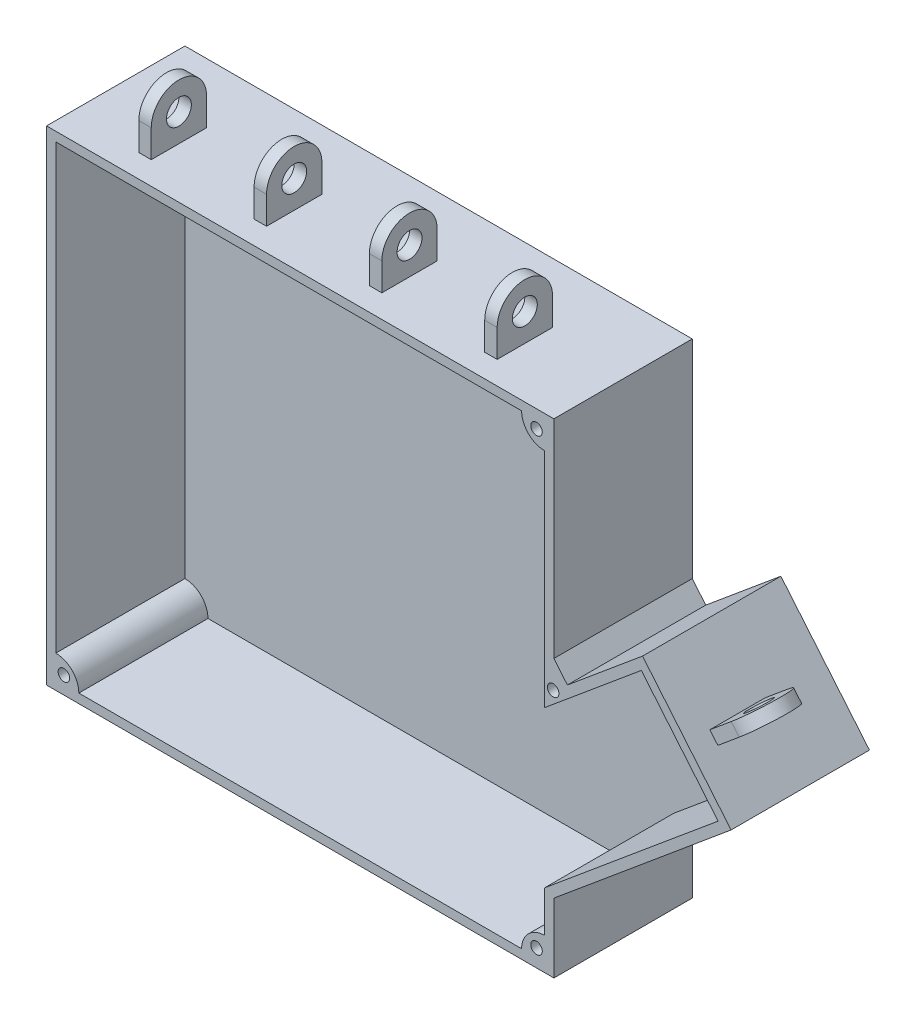
SolidWorks part; units mm, degrees
ref_plane "Front Plane" through (0, 0, 0) normal (0, 0, 1) x (1, 0, 0)
ref_plane "Top Plane" through (0, 0, 0) normal (0, 1, 0) x (1, 0, 0)
ref_plane "Right Plane" through (0, 0, 0) normal (1, 0, 0) x (0, 0, -1)
sketch "Sketch2" plane through (0, 0, 0) normal (0, 0, 1) x (1, 0, 0)
  line L0 (25, 95) -> (45, 95) construction
  line L1 (0, 0) -> (85, 0) construction
  line L2 (0, 0) -> (0, 50) construction
  line L3 (0, 50) -> (85, 50) construction
  line L4 (85, 0) -> (85, 50) construction
  line L5 (0, 95) -> (20, 95) construction
  line L6 (0, 95) -> (0, 55) construction
  line L7 (0, 55) -> (20, 55) construction
  line L8 (20, 95) -> (20, 55) construction
  line L9 (25, 95) -> (25, 55) construction
  line L10 (25, 55) -> (45, 55) construction
  line L11 (45, 95) -> (45, 55) construction
  line L12 (50, 95) -> (70, 95) construction
  line L13 (50, 95) -> (50, 55) construction
  line L14 (50, 55) -> (70, 55) construction
  line L15 (70, 95) -> (70, 55) construction
  line L16 (75, 95) -> (95, 95) construction
  line L17 (75, 95) -> (75, 55) construction
  line L18 (75, 55) -> (95, 55) construction
  line L19 (95, 95) -> (95, 55) construction
  line L24 (10, 95) -> (10, 55) construction
  line L26 (35, 95) -> (35, 55) construction
  line L28 (60, 95) -> (60, 55) construction
  line L29 (85, 95) -> (85, 55) construction
  dimension "D1" = 50
  dimension "D2" = 85
  dimension "D3" = 40
  dimension "D4" = 20
  dimension "D5" = 40
  dimension "D6" = 20
  dimension "D7" = 40
  dimension "D8" = 20
  dimension "D9" = 40
  dimension "D10" = 20
  dimension "D13" = 5
  dimension "D14" = 5
  dimension "D15" = 5
  dimension "D16" = 5
  dimension "D17" = 5
  dimension "D18" = 5
  dimension "D19" = 5
sketch "Sketch3" plane through (0, 0, 0) normal (0, 0, 1) x (1, 0, 0)
  line L0 (0, 0) -> (0, 50) construction
  line L9 (-5, -5) -> (105, -5)
  line L10 (-5, -5) -> (-5, 100)
  line L11 (-5, 100) -> (105, 100)
  line L12 (105, -5) -> (105, 10)
  line L13 (0, 0) -> (85, 0) construction
  line L14 (105, 10) -> (143.4182, 42.0006)
  line L15 (143.4182, 42.0006) -> (124.2179, 65.0515)
  line L16 (124.2179, 65.0515) -> (107.929, 51.4836)
  line L17 (107.929, 51.4836) -> (105, 55)
  line L18 (105, 55) -> (105, 100)
  dimension "D1" = 110
  dimension "D2" = 105
  dimension "D3" = 5
  dimension "D4" = 5
  dimension "D5" = 50
  dimension "D6" = 15
  dimension "D7" = 45
  dimension "D8" = 30
extrude "Boss-Extrude1" add sketch "Sketch3" along normal blind 30
sketch "Sketch4" plane through (0, 0, 0) normal (1, 0, 0) x (0, 0, -1)
  line L0 (-30, 100) -> (0, 100) construction
  line L1 (-25, 100) -> (-13, 100)
  line L2 (-25, 100) -> (-25, 106)
  line L4 (-13, 100) -> (-13, 106)
  line L5 (-30, 55) -> (-30, 100) construction
  arc A2 (-13, 106) -> (-25, 106) centre (-19, 106) ccw
  circle A3 centre (-19, 106) radius 2.7
  dimension "D4" = 5.4
  dimension "D1" = 5
  dimension "D2" = 6
  dimension "D3" = 12
shell "Shell1" thickness 2
sketch "Sketch9" plane through (0, 0, 2) normal (0, 0, 1) x (1, 0, 0)
  line L4 (92.8415, 32.4092) -> (123.5761, 58.0097) construction
  line L5 (123.5761, 58.0097) -> (136.3764, 42.6424) construction
  line L6 (136.3764, 42.6424) -> (105.6418, 17.0419) construction
  line L7 (105.6418, 17.0419) -> (92.8415, 32.4092) construction
  line L11 (140.6015, 42.2573) -> (123.9612, 62.2348) construction
  line L12 (123.9612, 62.2348) -> (107.6723, 48.6669) construction
  line L13 (129.9762, 50.326) -> (99.2416, 24.7255) construction
  dimension "D1" = 20
  dimension "D2" = 3
  dimension "D3" = 3
  dimension "D4" = 40
ref_plane "Plane6" through (0, 0, 30) normal (0, 0, 1) x (1, 0, 0)
sketch "Sketch10" plane through (0, 0, 30) normal (0, 0, 1) x (1, 0, 0)
  line L0 (103, 98) -> (-3, 98) construction
  line L1 (-3, 98) -> (-3, -3) construction
  line L2 (103, 54.2762) -> (103, 98) construction
  line L3 (103, -3) -> (103, 10.937) construction
  line L4 (-3, -3) -> (103, -3) construction
  line L5 (-3, -3) -> (103, -3) construction
  line L6 (98, 98) -> (103, 98)
  line L7 (103, 98) -> (103, 93)
  line L8 (103, 2) -> (103, -3)
  line L9 (103, -3) -> (98, -3)
  line L10 (-3, 2) -> (-3, -3)
  line L11 (-3, -3) -> (2, -3)
  line L12 (-3, -3) -> (0.5355, 0.5355) construction
  line L13 (103, -3) -> (99.4645, 0.5355) construction
  line L14 (103, 98) -> (99.4645, 94.4645) construction
  line L15 (103, 54.2762) -> (103, 44.7751)
  line L17 (103, 54.2762) -> (107.6723, 48.6669)
  line L18 (107.6723, 48.6669) -> (103, 44.7751)
  circle A0 centre (-1.2322, -1.2322) radius 1.25
  arc A1 (103, 93) -> (98, 98) centre (103, 98) cw
  arc A2 (103, 2) -> (98, -3) centre (103, -3) ccw
  arc A3 (-3, 2) -> (2, -3) centre (-3, -3) cw
  circle A4 centre (101.2322, -1.2322) radius 1.25
  circle A5 centre (101.2322, 96.2322) radius 1.25
  circle A7 centre (104.8383, 48.9443) radius 1.25
  dimension "D1" = 5
  dimension "D4" = 2.5
  dimension "D5" = 2.5
  dimension "D6" = 2.5
  dimension "D7" = 2.5
  dimension "D8" = 2
  dimension "D2" = 5
  dimension "D3" = 5
extrude "Boss-Extrude8" add sketch "Sketch10" along normal through all from surface
ref_plane "Plane9" through (10, 0, 0) normal (1, 0, 0) x (0, 0, -1)
extrude "Boss-Extrude10" add sketch "Sketch4" along normal blind 2.7 from surface at 10 starting at plane "Plane9"
pattern_linear "LPattern1" count 4 spacing 25 along (1, 0, 0) of "Boss-Extrude10"
ref_plane "Plane11" through (28.4918, -34.2058, 0) normal (0.64, -0.7684, 0) x (-0.7684, -0.64, 0)
sketch "Sketch15" plane through (28.4918, -34.2058, 0) normal (0.64, -0.7684, 0) x (-0.7684, -0.64, 0)
  line L0 (-137.0784, -13) -> (-143.0784, -13)
  line L1 (-137.0784, -30) -> (-137.0784, 0) construction
  line L2 (-137.0784, -13) -> (-137.0784, -25)
  line L3 (-137.0784, -25) -> (-143.0784, -25)
  line L4 (-143.0784, -13) -> (-143.0784, -25) construction
  line L5 (-57.75, -30) -> (57.75, -30) construction
  arc A0 (-143.0784, -25) -> (-143.0784, -13) centre (-143.0784, -19) cw
  circle A1 centre (-143.0784, -19) radius 2.7
  dimension "D2" = 12
  dimension "D4" = 5.4
  dimension "D3" = 6
  dimension "D5" = 5
extrude "Boss-Extrude11" add sketch "Sketch15" along normal blind 2.7
